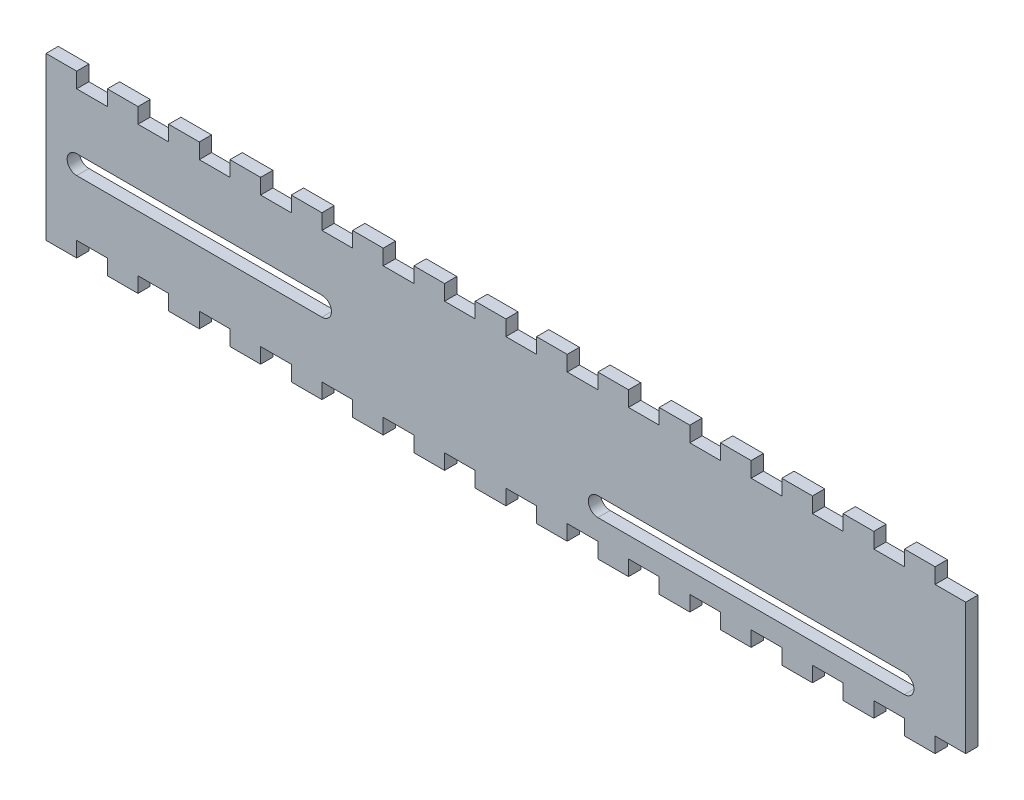
SolidWorks part; units mm, degrees
ref_plane "Front Plane" through (0, 0, 0) normal (0, 0, 1) x (1, 0, 0)
ref_plane "Top Plane" through (0, 0, 0) normal (0, 1, 0) x (1, 0, 0)
ref_plane "Right Plane" through (0, 0, 0) normal (1, 0, 0) x (0, 0, -1)
sketch "Sketch1" plane through (0, 0, 0) normal (0, 0, 1) x (1, 0, 0)
  line L0 (0, 10.7) -> (150, 10.7) construction
  line L1 (0, 0) -> (150, 0)
  line L2 (0, 0) -> (0, 21.4)
  line L3 (0, 21.4) -> (150, 21.4)
  line L4 (150, 0) -> (150, 21.4)
  dimension "D5" = 21.4
  dimension "D8" = 150
extrude "Boss-Extrude2" add sketch "Sketch1" along normal blind 2
sketch "Sketch2" plane through (0, 21.4, 0) normal (0, 1, 0) x (1, 0, 0)
  line L1 (0, 0) -> (150, 0) construction
  line L2 (0, 0) -> (5, 0)
  line L3 (0, 0) -> (0, -2)
  line L4 (0, -2) -> (5, -2)
  line L5 (5, 0) -> (5, -2)
  line L6 (0, -2) -> (150, -2) construction
  line L7 (0, -2) -> (0, 0) construction
  dimension "D1" = 5
  dimension "D2" = 0
extrude "Boss-Extrude3" add sketch "Sketch2" along normal blind 2.5
pattern_linear "LPattern1" count 15 spacing 10 along (1, 0, 0) of "Boss-Extrude3"
sketch "Sketch3" plane through (0, 0, 0) normal (0, -1, 0) x (-1, 0, 0)
  line L1 (0, -2) -> (-150, -2) construction
  line L2 (0, -2) -> (-5, -2)
  line L3 (0, -2) -> (0, 0)
  line L4 (0, 0) -> (-5, 0)
  line L5 (-5, -2) -> (-5, 0)
  line L6 (0, 0) -> (-150, 0) construction
  line L7 (0, -2) -> (0, 0) construction
  point P9 (0, -1)
  dimension "D1" = 5
  dimension "D2" = 0
extrude "Boss-Extrude4" add sketch "Sketch3" along normal blind 2.5
pattern_linear "LPattern2" count 15 spacing 10 along (1, 0, 0) of "Boss-Extrude4"
sketch "Sketch4" plane through (0, 0, 0) normal (0, 0, -1) x (-1, 0, 0)
  line L0 (-140, 4.9) -> (-90, 4.9) construction
  line L1 (-140, 6.45) -> (-90, 6.45)
  line L2 (-140, 3.35) -> (-90, 3.35)
  line L3 (-150, 0) -> (-150, 21.4) construction
  line L4 (-150, 0) -> (-150, 21.4) construction
  line L5 (-115, 21.4) -> (-120, 21.4) construction
  line L6 (0, 10.7) -> (-150, 10.7) construction
  line L7 (0, -2.5) -> (0, 23.9) construction
  line L8 (-45, 10.7) -> (-5, 10.7) construction
  line L9 (-45, 12.25) -> (-5, 12.25)
  line L10 (-45, 9.15) -> (-5, 9.15)
  line L16 (-15, 21.4) -> (-20, 21.4) construction
  arc A0 (-140, 6.45) -> (-140, 3.35) centre (-140, 4.9) ccw
  arc A1 (-90, 3.35) -> (-90, 6.45) centre (-90, 4.9) ccw
  arc A2 (-45, 12.25) -> (-45, 9.15) centre (-45, 10.7) ccw
  arc A3 (-5, 9.15) -> (-5, 12.25) centre (-5, 10.7) ccw
  point P2 (-115, 4.9)
  point P19 (-25, 10.7)
  dimension "D2" = 1.55
  dimension "D7" = 1.55
  dimension "D1" = 10
  dimension "D3" = 50
  dimension "D4" = 16.5
  dimension "D5" = 40
  dimension "D6" = 5
  dimension "D8" = 10.7
extrude "Cut-Extrude1" cut sketch "Sketch4" against normal blind 10
